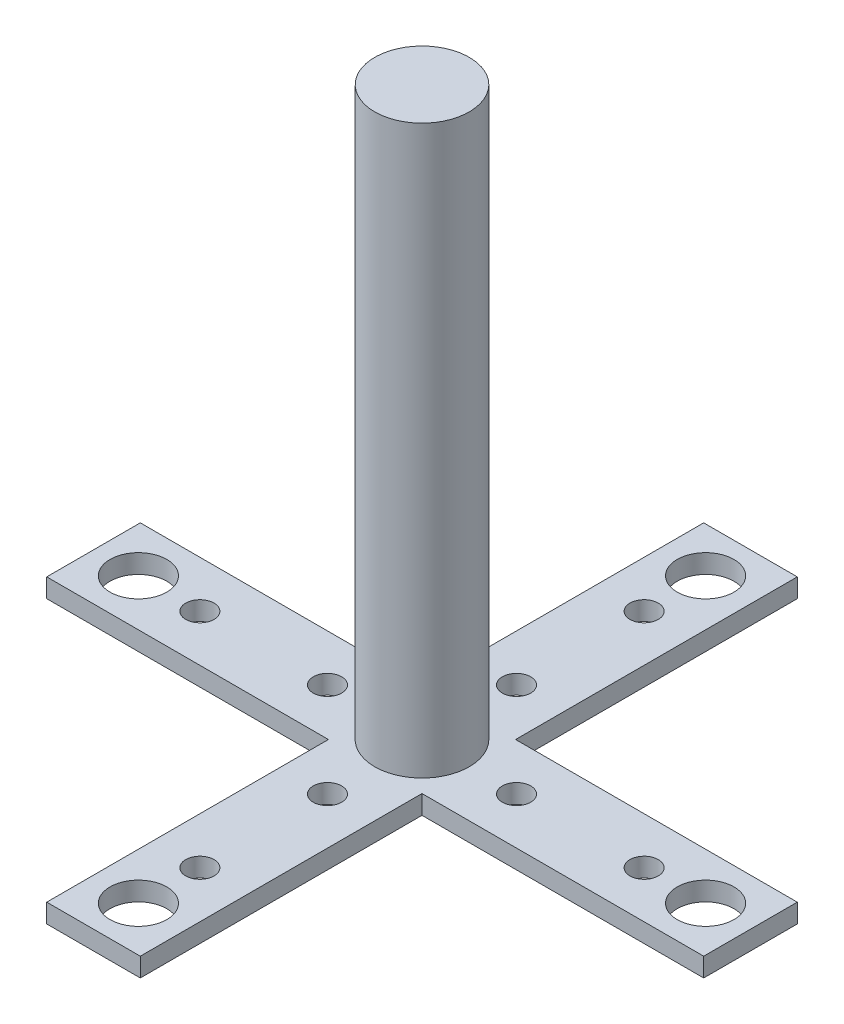
SolidWorks part; units mm, degrees
ref_plane "前视基准面" through (0, 0, 0) normal (0, 0, 1) x (1, 0, 0)
ref_plane "上视基准面" through (0, 0, 0) normal (0, 1, 0) x (1, 0, 0)
ref_plane "右视基准面" through (0, 0, 0) normal (1, 0, 0) x (0, 0, -1)
other "Configuration Table"
sketch "草图2" plane through (0, 0, 0) normal (0, 1, 0) x (1, 0, 0)
  line L0 (-5, 15) -> (35350.3391, -35340.3391) construction
  line L1 (-34.75, -4.95) -> (34.75, -4.95)
  line L2 (-34.75, -4.95) -> (-34.75, 4.95)
  line L3 (-34.75, 4.95) -> (34.75, 4.95)
  line L4 (34.75, -4.95) -> (34.75, 4.95)
  line L5 (-34.75, -4.95) -> (34.75, 4.95) construction
  line L6 (-34.75, 4.95) -> (34.75, -4.95) construction
  line L7 (-4.95, -34.75) -> (4.95, -34.75)
  line L8 (-4.95, -34.75) -> (-4.95, 34.75)
  line L9 (-4.95, 34.75) -> (4.95, 34.75)
  line L10 (4.95, -34.75) -> (4.95, 34.75)
  line L11 (-4.95, -34.75) -> (4.95, 34.75) construction
  line L12 (-4.95, 34.75) -> (4.95, -34.75) construction
  line L17 (-15, -5) -> (15, 5) construction
  line L18 (-15, 5) -> (15, -5) construction
  line L23 (-5, -15) -> (5, 15) construction
  line L24 (-5, 15) -> (5, -15) construction
  line L25 (5, 15) -> (-35350.3391, -35340.3391) construction
  line L27 (-5, -35) -> (5, -35)
  line L29 (-5, 35) -> (5, 35)
  line L31 (-5, -35) -> (5, 35) construction
  line L32 (-5, 35) -> (5, -35) construction
  circle A0 centre (0, 0) radius 5
  circle A1 centre (0, 10) radius 1.5
  circle A2 centre (0, 30) radius 3
  circle A3 centre (0, 23.5) radius 1.5
  circle A4 centre (23.5, 0) radius 1.5
  circle A5 centre (10, 0) radius 1.5
  circle A6 centre (0, -23.5) radius 1.5
  circle A7 centre (0, -10) radius 1.5
  circle A8 centre (-23.5, 0) radius 1.5
  circle A9 centre (-10, 0) radius 1.5
  point P0 (0, 0)
  point P6 (0, 0)
  point P35 (0, 35)
  dimension "D5" = 10
  dimension "D10" = 3
  dimension "D13" = 6
  dimension "D14" = 3
  dimension "D1" = 69.5
  dimension "D2" = 9.9
  dimension "D3" = 9.9
  dimension "D4" = 69.5
  dimension "D6" = 30
  dimension "D7" = 70
  dimension "D8" = 10
  dimension "D9" = 30
  dimension "D11" = 10
  dimension "D12" = 5
  dimension "D15" = 11.5
  dimension "D16" = 4
extrude "凸台-拉伸5" add sketch "草图2" along normal blind 2 contours A0 L8 L3 L2 L1 A9 A8 | A0 L3 L10 L9 L8 A3 A2 A1 | A0 L10 L1 L4 L3 A5 A4 | A0 L1 L8 L7 L10 A7 A6 | L1 A0 L10 L3 L8 | A0 L3 L8 | A0 L8 L1 | A0 L10 L3 | A0 L1 L10 | A2
sketch "草图4" plane through (0, 2, 0) normal (0, 1, 0) x (1, 0, 0)
  circle A0 centre (0, 0) radius 5
  dimension "D1" = 10
extrude "凸台-拉伸8" add sketch "草图4" along normal blind 60
sketch "草图6" plane through (0, 0, 0) normal (0, -1, 0) x (1, 0, 0)
  circle A0 centre (0, -30) radius 3
  circle A1 centre (-30, 0) radius 3
  circle A2 centre (0, 30) radius 3
  circle A3 centre (30, 0) radius 3
  point P12 (0, 0)
  dimension "D1" = 4
extrude "切除-拉伸1" cut sketch "草图6" against normal through all
